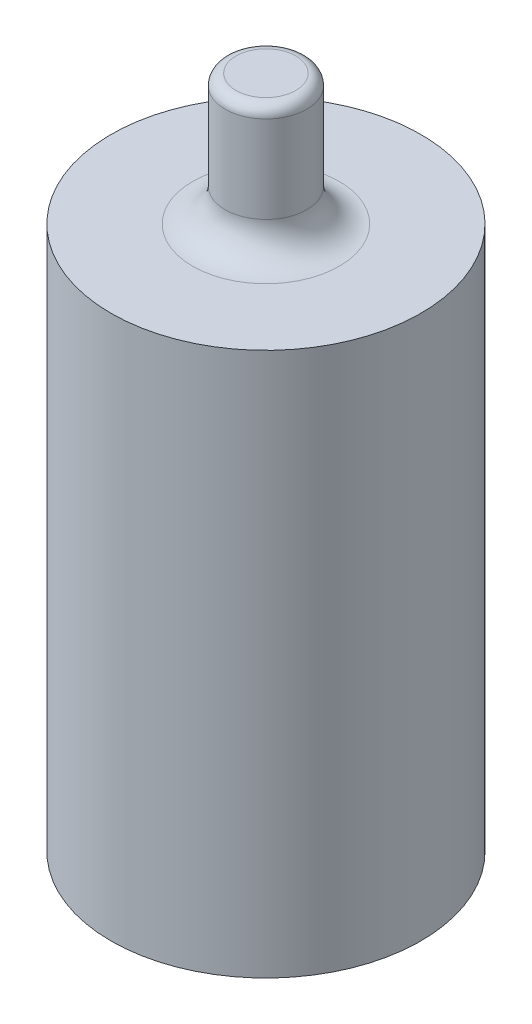
SolidWorks part; units mm, degrees
ref_plane "Ön Düzlem" through (0, 0, 0) normal (0, 0, 1) x (1, 0, 0)
ref_plane "Üst Düzlem" through (0, 0, 0) normal (0, 1, 0) x (1, 0, 0)
ref_plane "Sağ Düzlem" through (0, 0, 0) normal (1, 0, 0) x (0, 0, -1)
sketch "Çizim3" plane through (0, 0, 0) normal (0, 1, 0) x (1, 0, 0)
  circle A0 centre (0, 0) radius 14.25
  dimension "D1" = 28.5
extrude "Yükseklik-Ekstrüzyon2" add sketch "Çizim3" along normal blind 50
sketch "Çizim4" plane through (0, 50, 0) normal (0, 1, 0) x (1, 0, 0)
  circle A0 centre (0, 0) radius 3.75
  dimension "D1" = 7.5
extrude "Yükseklik-Ekstrüzyon3" add sketch "Çizim4" along normal blind 12
fillet "Radyus1" radius 3 1 edges at (0, 50, 3.75)
fillet "Radyus2" radius 1 1 edges at (0, 62, 3.75)
sketch "Çizim5" plane through (0, 0, 0) normal (0, -1, 0) x (1, 0, 0)
  circle A0 centre (0, 0) radius 12.6354
extrude "Kes-Ekstrüzyon1" cut sketch "Çizim5" against normal blind 47
